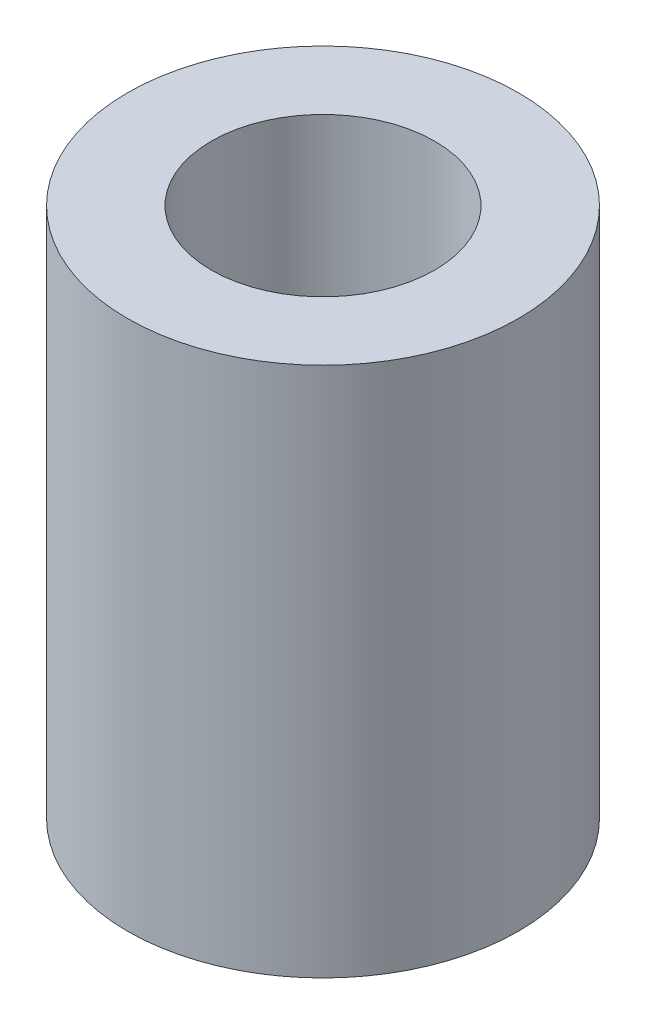
SolidWorks part; units mm, degrees
material "PLA"
ref_plane "Front Plane" through (0, 0, 0) normal (0, 0, 1) x (1, 0, 0)
ref_plane "Top Plane" through (0, 0, 0) normal (0, 1, 0) x (1, 0, 0)
ref_plane "Right Plane" through (0, 0, 0) normal (1, 0, 0) x (0, 0, -1)
ref_plane "Plane1" through (0, 0, 0) normal (0, 1, 0) x (1, 0, 0)
sketch "Sketch1" plane through (0, 0, 0) normal (0, 1, 0) x (1, 0, 0)
  circle A0 centre (0, 0) radius 3.5
  circle A1 centre (0, 0) radius 2
  dimension "D1" = 4
  dimension "D2" = 7
extrude "Boss-Extrude1" add sketch "Sketch1" along normal blind 9.5
